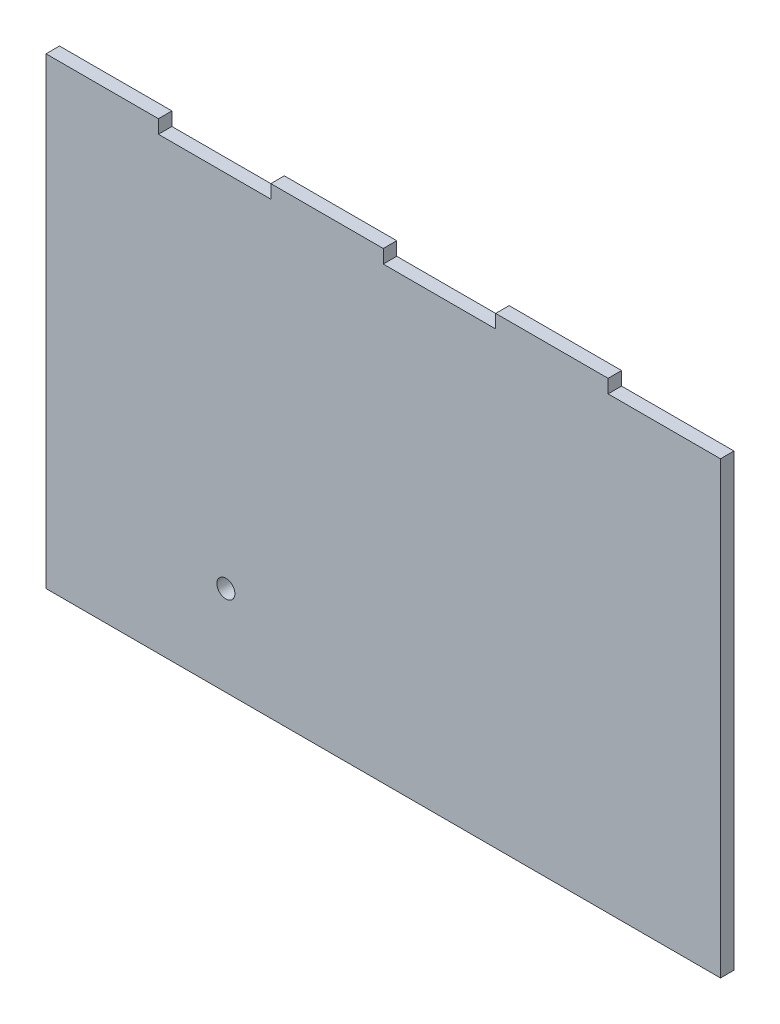
SolidWorks part; units mm, degrees
material "Perspex (TM) Plaque acrylique coulée"
ref_plane "Plan de face" through (0, 0, 0) normal (0, 0, 1) x (1, 0, 0)
ref_plane "Plan de dessus" through (0, 0, 0) normal (0, 1, 0) x (1, 0, 0)
ref_plane "Plan de droite" through (0, 0, 0) normal (1, 0, 0) x (0, 0, -1)
sketch "Esquisse1" plane through (0, 0, 0) normal (0, 0, 1) x (1, 0, 0)
  line L0 (0, 200) -> (0, 206)
  line L1 (0, 0) -> (300, 0)
  line L2 (0, 0) -> (0, 200)
  line L4 (300, 0) -> (300, 200)
  line L5 (0, 206) -> (50, 206)
  line L6 (50, 206) -> (50, 200)
  line L7 (50, 200) -> (100, 200)
  line L8 (100, 200) -> (100, 206)
  line L9 (100, 206) -> (150, 206)
  line L10 (150, 206) -> (150, 200)
  line L11 (150, 200) -> (200, 200)
  line L12 (200, 200) -> (200, 206)
  line L13 (200, 206) -> (250, 206)
  line L14 (250, 206) -> (250, 200)
  line L15 (250, 200) -> (300, 200)
  circle A0 centre (80, 40) radius 4
  dimension "D5" = 8
  dimension "D1" = 200
  dimension "D2" = 300
  dimension "D3" = 40
  dimension "D4" = 80
  dimension "D6" = 50
  dimension "D7" = 6
  dimension "D8" = 50
  dimension "5" = 6
  dimension "D9" = 6
  dimension "D10" = 6
  dimension "D11" = 50
  dimension "D12" = 50
  dimension "D13" = 6
  dimension "D14" = 50
extrude "Boss.-Extru.1" add sketch "Esquisse1" along normal blind 6
